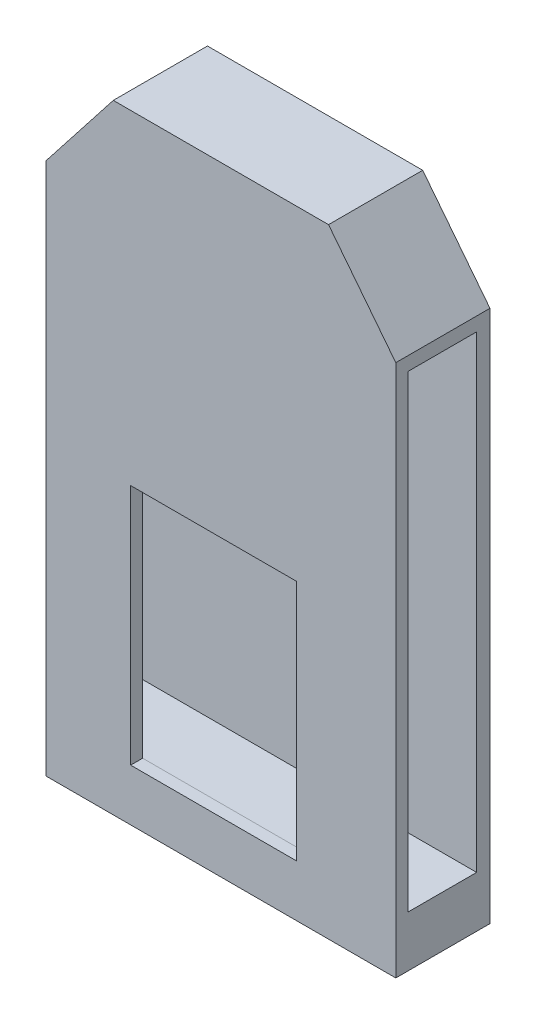
SolidWorks part; units mm, degrees
ref_plane "Front Plane" through (0, 0, 0) normal (0, 0, 1) x (1, 0, 0)
ref_plane "Top Plane" through (0, 0, 0) normal (0, 1, 0) x (1, 0, 0)
ref_plane "Right Plane" through (0, 0, 0) normal (1, 0, 0) x (0, 0, -1)
sketch "Sketch1" plane through (0, 0, 0) normal (0, 0, 1) x (1, 0, 0)
  line L2 (130, -230) -> (-130, -230)
  line L3 (-130, -230) -> (-130, 166.14)
  line L4 (80, 230) -> (-80, 230)
  line L6 (-130, 166.14) -> (-80, 230)
  line L7 (130, 166.14) -> (80, 230)
  line L8 (130, -230) -> (130, 166.14)
  dimension "D1" = 396.14
  dimension "D2" = 260
  dimension "D3" = 160
  dimension "D4" = 50
  dimension "D5" = 63.86
  dimension "D6" = 81.1055
extrude "Boss-Extrude1" add sketch "Sketch1" along normal blind 70
sketch "Sketch2" plane through (0, 0, 70) normal (0, 0, 1) x (1, 0, 0)
  line L5 (-67.1, -191.52) -> (56.15, -191.52)
  line L6 (-67.1, -191.52) -> (-67.1, -11.52)
  line L7 (-67.1, -11.52) -> (56.15, -11.52)
  line L8 (56.15, -191.52) -> (56.15, -11.52)
  dimension "D1" = 180
  dimension "D2" = 123.25
extrude "Cut-Extrude1" cut sketch "Sketch2" against normal blind 60
sketch "Sketch3" plane through (0, -11.52, 0) normal (0, -1, 0) x (1, 0, 0)
  line L9 (52.6555, 67.4802) -> (-63.6055, 67.4802)
  line L10 (52.6555, 67.4802) -> (52.6555, 12.5198)
  line L11 (52.6555, 12.5198) -> (-63.6055, 12.5198)
  line L12 (-63.6055, 67.4802) -> (-63.6055, 12.5198)
  point P9 (-5.475, 40)
  dimension "D1" = 54.9605
  dimension "D2" = 116.2609
extrude "Cut-Extrude2" cut sketch "Sketch3" against normal blind 232
sketch "Sketch4" plane through (-130, 0, 0) normal (-1, 0, 0) x (0, 0, 1)
  line L5 (9.89, -192.07) -> (61.07, -192.07)
  line L6 (9.89, -192.07) -> (9.89, 155.96)
  line L7 (9.89, 155.96) -> (61.07, 155.96)
  line L8 (61.07, -192.07) -> (61.07, 155.96)
  dimension "D1" = 348.03
  dimension "D2" = 51.18
extrude "Cut-Extrude3" cut sketch "Sketch4" against normal blind 260
